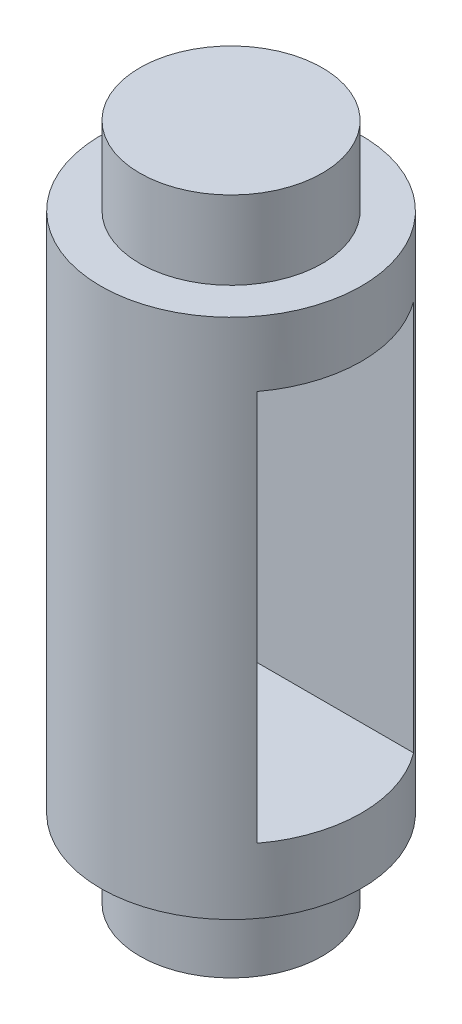
SolidWorks part; units mm, degrees
ref_plane "Alzado" through (0, 0, 0) normal (0, 0, 1) x (1, 0, 0)
ref_plane "Planta" through (0, 0, 0) normal (0, 1, 0) x (1, 0, 0)
ref_plane "Vista lateral" through (0, 0, 0) normal (1, 0, 0) x (0, 0, -1)
sketch "Croquis1" plane through (0, 0, 0) normal (0, 1, 0) x (1, 0, 0)
  circle A0 centre (0, 0) radius 3.5
  dimension "D1" = 7
extrude "Saliente-Extruir1" add sketch "Croquis1" along normal blind 3
sketch "Croquis2" plane through (0, 3, 0) normal (0, 1, 0) x (1, 0, 0)
  circle A0 centre (0, 0) radius 5
  dimension "D1" = 10
extrude "Saliente-Extruir2" add sketch "Croquis2" along normal blind 20
sketch "Croquis3" plane through (0, 23, 0) normal (0, 1, 0) x (1, 0, 0)
  circle A0 centre (0, 0) radius 3.5
  dimension "D1" = 7
extrude "Saliente-Extruir3" add sketch "Croquis3" along normal blind 3
sketch "Croquis4" plane through (0, 0, 0) normal (1, 0, 0) x (0, 0, -1)
  line L0 (0, 26) -> (0, 0) construction
  line L1 (-3, 20.5) -> (3, 20.5)
  line L2 (-3, 20.5) -> (-3, 5.5)
  line L3 (-3, 5.5) -> (3, 5.5)
  line L4 (3, 20.5) -> (3, 5.5)
  line L5 (3.5, 26) -> (-3.5, 26) construction
  line L6 (-3.5, 0) -> (3.5, 0) construction
  line L7 (5, 23) -> (-5, 23) construction
  point P10 (0, 20.5)
  dimension "D1" = 6
  dimension "D2" = 2.5
  dimension "D3" = 15
extrude "Cortar-Extruir1" cut sketch "Croquis4" against normal blind 11 and the other way blind 10
